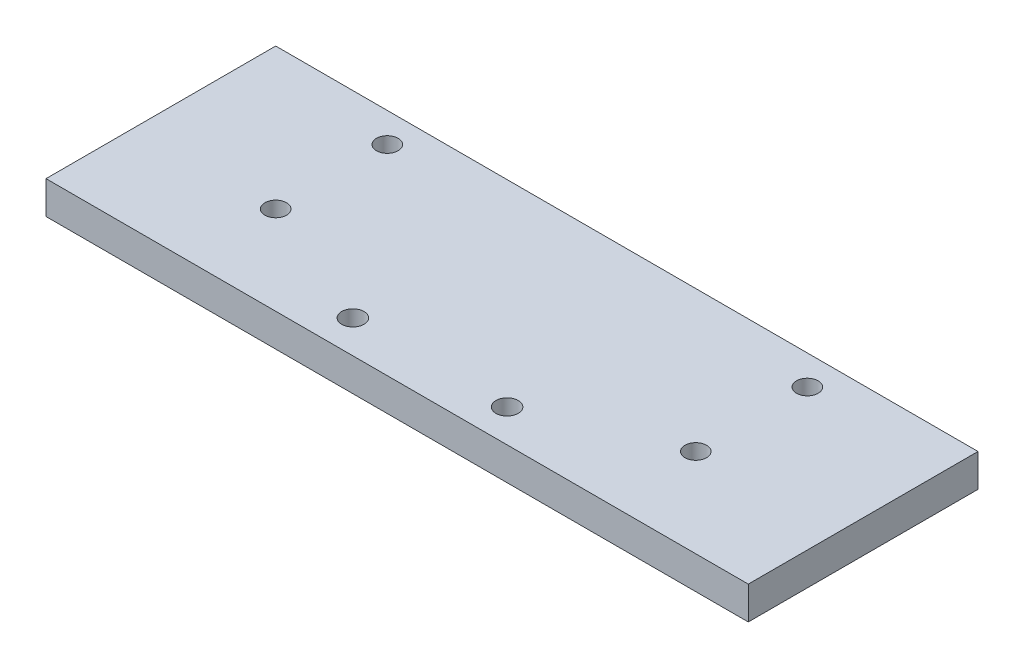
SolidWorks part; units mm, degrees
ref_plane "前视基准面" through (0, 0, 0) normal (0, 0, 1) x (1, 0, 0)
ref_plane "上视基准面" through (0, 0, 0) normal (0, 1, 0) x (1, 0, 0)
ref_plane "右视基准面" through (0, 0, 0) normal (1, 0, 0) x (0, 0, -1)
sketch "草图1" plane through (0, 0, 0) normal (0, 1, 0) x (1, 0, 0)
  line L1 (-34.4497, 13.4827) -> (72.5503, 13.4827)
  line L2 (-34.4497, 13.4827) -> (-34.4497, -21.5173)
  line L3 (-34.4497, -21.5173) -> (72.5503, -21.5173)
  line L4 (72.5503, 13.4827) -> (72.5503, -21.5173)
  dimension "D1" = 35
  dimension "D2" = 107
extrude "凸台-拉伸1" add sketch "草图1" along normal blind 5 contours L1 L4 L3 L2
sketch "草图2" plane through (0, 5, 0) normal (0, 1, 0) x (1, 0, 0)
  line L0 (19.0503, 13.4827) -> (19.0503, -21.5173) construction
  line L1 (-34.4497, 13.4827) -> (72.5503, 13.4827) construction
  line L2 (-34.4497, -21.5173) -> (72.5503, -21.5173) construction
  line L3 (-34.4497, 0.4827) -> (72.1309, 0.4827) construction
  line L4 (-34.4497, 13.4827) -> (-34.4497, -21.5173) construction
  circle A0 centre (7.3003, -16.5173) radius 1.7
  circle A1 centre (-12.9497, 8.9827) radius 1.65
  circle A2 centre (-12.9497, -8.0173) radius 1.65
  circle A3 centre (30.8003, -16.5173) radius 1.7
  circle A4 centre (51.0503, -8.0173) radius 1.65
  circle A5 centre (51.0503, 8.9827) radius 1.65
  dimension "D2" = 3.4
  dimension "D4" = 3.3
  dimension "D1" = 11.75
  dimension "D3" = 5
  dimension "D5" = 8.5
  dimension "D6" = 32
  dimension "D7" = 13
extrude "切除-拉伸1" cut sketch "草图2" against normal blind 5 contours A0 | A2 | A1 | A5 | A4 | A3
